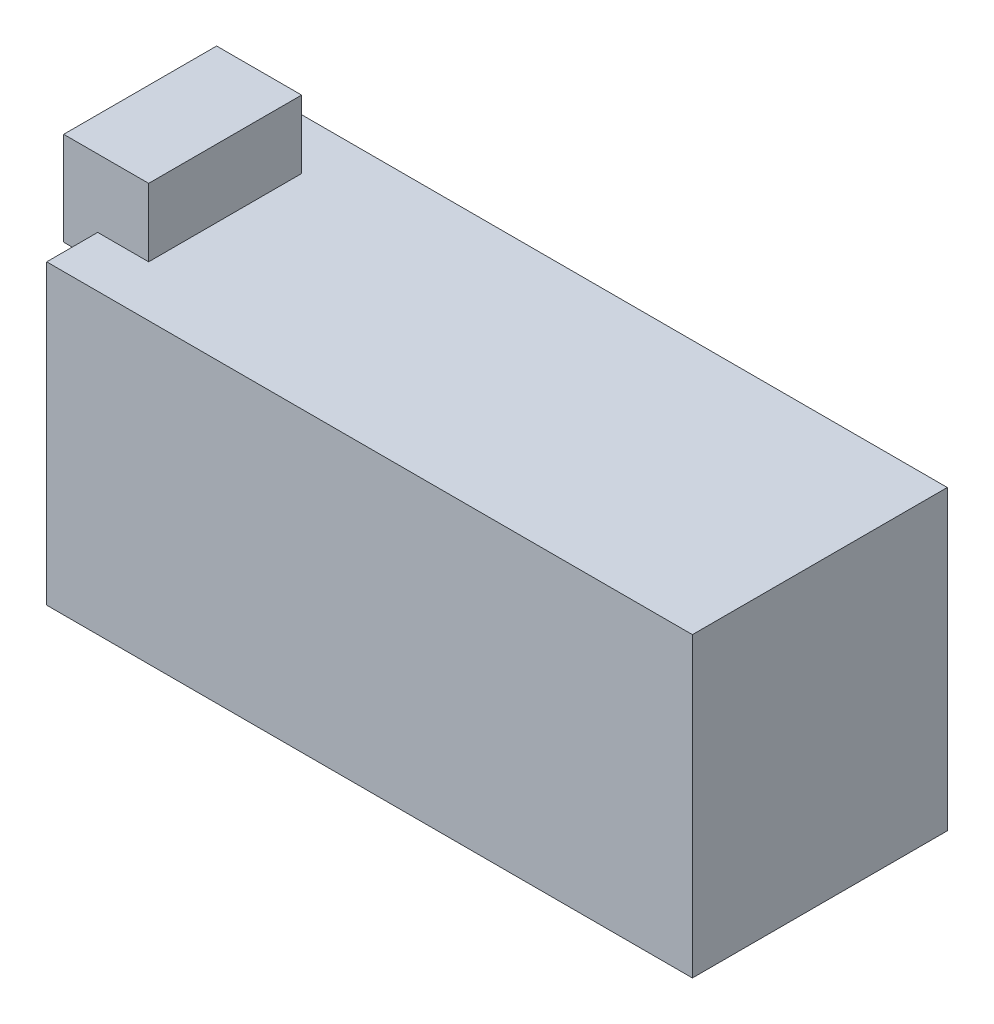
SolidWorks part; units mm, degrees
ref_plane "Front Plane" through (0, 0, 0) normal (0, 0, 1) x (1, 0, 0)
ref_plane "Top Plane" through (0, 0, 0) normal (0, 1, 0) x (1, 0, 0)
ref_plane "Right Plane" through (0, 0, 0) normal (1, 0, 0) x (0, 0, -1)
sketch "Sketch1" plane through (0, 0, 0) normal (0, 0, 1) x (1, 0, 0)
  line L1 (-38, -17.5) -> (38, -17.5)
  line L2 (-38, -17.5) -> (-38, 17.5)
  line L3 (-38, 17.5) -> (38, 17.5)
  line L4 (38, -17.5) -> (38, 17.5)
  line L5 (-38, -17.5) -> (38, 17.5) construction
  line L6 (-38, 17.5) -> (38, -17.5) construction
  point P0 (0, 0)
  dimension "D1" = 76
  dimension "D2" = 35
extrude "Boss-Extrude1" add sketch "Sketch1" along normal blind 30
sketch "Sketch2" plane through (0, 17.5, 0) normal (0, 1, 0) x (1, 0, 0)
  line L0 (38, 0) -> (-38, 0) construction
  line L1 (-42, -6) -> (-32, -6)
  line L2 (-42, -6) -> (-42, -24)
  line L3 (-42, -24) -> (-32, -24)
  line L4 (-32, -6) -> (-32, -24)
  line L5 (-38, -30) -> (-38, 0) construction
  dimension "D1" = 18
  dimension "D2" = 6
  dimension "D3" = 10
  dimension "D4" = 6
extrude "Boss-Extrude2" add sketch "Sketch2" along normal blind 8 and the other way blind 3
